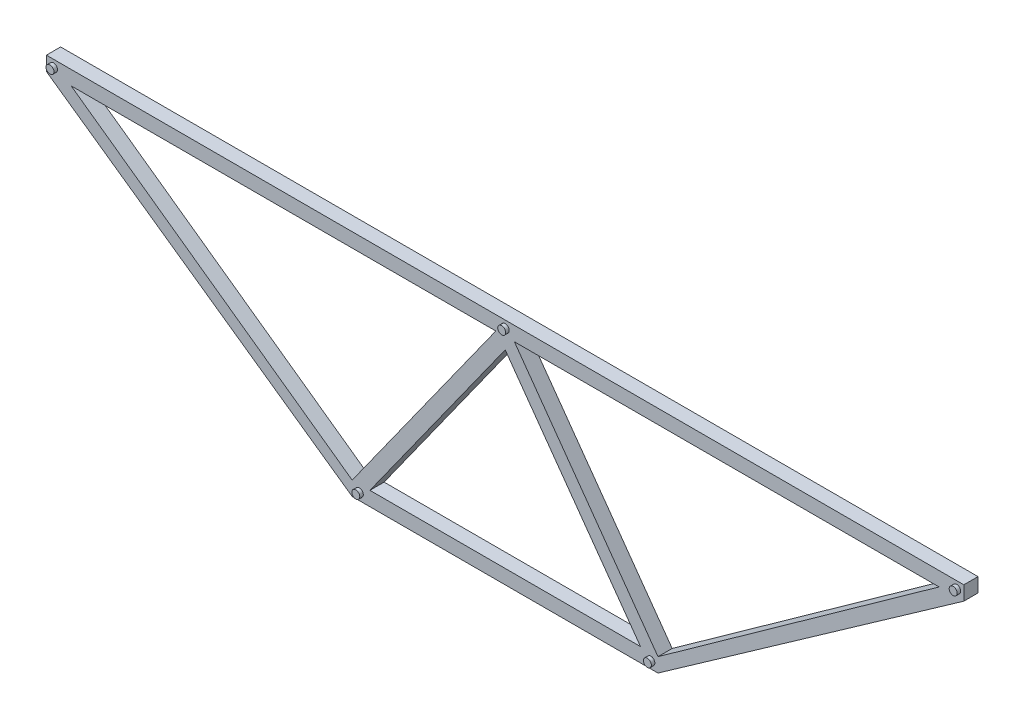
SolidWorks part; units mm, degrees
material "A 500 STEEL"
ref_plane "Front Plane" through (0, 0, 0) normal (0, 0, 1) x (1, 0, 0)
ref_plane "Top Plane" through (0, 0, 0) normal (0, 1, 0) x (1, 0, 0)
ref_plane "Right Plane" through (0, 0, 0) normal (1, 0, 0) x (0, 0, -1)
sketch "Sketch2" plane through (0, 0, 0) normal (0, 0, 1) x (1, 0, 0)
  line L0 (0, 0) -> (1200, 0)
  line L1 (0, 0) -> (0, -18.59)
  line L2 (0, -18.59) -> (400, -300)
  line L3 (400, -300) -> (800, -300)
  line L4 (800, -300) -> (1200, -18.59)
  line L5 (1200, -18.59) -> (1200, 0)
  dimension "D1" = 1200
  dimension "D2" = 18.59
  dimension "D3" = 300
  dimension "D4" = 400
extrude "Boss-Extrude1" add sketch "Sketch2" along normal blind 18.59
sketch "Sketch3" plane through (0, 0, 18.59) normal (0, 0, 1) x (1, 0, 0)
  line L0 (32.3082, 0) -> (32.3082, -18.59) construction
  line L1 (1200, 0) -> (0, 0) construction
  line L2 (21.6116, -33.7943) -> (32.3082, -18.59) construction
  line L3 (0, -18.59) -> (400, -300) construction
  line L6 (400, -300) -> (400, -281.41) construction
  line L7 (32.3082, -18.59) -> (400, -281.41)
  line L8 (400, -281.41) -> (587.8594, -18.59)
  line L9 (587.8594, -18.59) -> (32.3082, -18.59)
  line L12 (556.1658, -62.9301) -> (571.2896, -73.7403) construction
  line L13 (600.1563, -33.7923) -> (423.1633, -281.41)
  line L14 (800, -300) -> (800, -281.41) construction
  line L15 (1178.3884, -33.7943) -> (1167.6918, -18.59) construction
  line L16 (800, -300) -> (1200, -18.59) construction
  line L17 (800, -281.41) -> (1167.6918, -18.59)
  line L18 (633.8432, -48.9525) -> (618.7195, -59.7627) construction
  line L19 (800, -281.41) -> (612.1406, -18.59)
  line L20 (612.1406, -18.59) -> (1167.6918, -18.59)
  line L21 (671.7379, -281.41) -> (671.7379, -300) construction
  line L22 (777.1493, -281.41) -> (423.1633, -281.41)
  line L23 (767.4609, 0) -> (767.4609, -18.59) construction
  line L24 (400, -300) -> (800, -300) construction
  line L25 (777.1493, -281.41) -> (600.1563, -33.7923)
  point P31 (589.5383, -18.59)
  point P33 (618.3916, -59.9931)
  point P34 (571.2896, -73.7403)
  dimension "D1" = 18.59
  dimension "D2" = 18.59
  dimension "D3" = 18.59
  dimension "D4" = 18.59
  dimension "D5" = 18.59
  dimension "D6" = 18.59
  dimension "D7" = 18.59
  dimension "D8" = 18.59
  dimension "D9" = 18.59
extrude "Cut-Extrude2" cut sketch "Sketch3" against normal through all
sketch "Sketch4" plane through (0, 0, 0) normal (0, 0, -1) x (-1, 0, 0)
  line L0 (-1200, 0) -> (0, 0) construction
  line L1 (-1200, -18.59) -> (-1200, 0) construction
  line L2 (0, 0) -> (0, -18.59) construction
  line L3 (-400, -300) -> (-800, -300) construction
  circle A0 centre (-1190.705, -9.295) radius 5.207
  circle A1 centre (-600.1563, -9.295) radius 5.207
  circle A2 centre (-9.295, -9.295) radius 5.207
  circle A3 centre (-790.705, -290.705) radius 5.207
  circle A4 centre (-409.295, -290.705) radius 5.207
  dimension "D3" = 10.414
  dimension "D4" = 9.295
  dimension "D1" = 9.295
  dimension "D2" = 9.295
  dimension "D5" = 9.295
  dimension "D6" = 9.295
  dimension "D7" = 9.295
extrude "Boss-Extrude3" add sketch "Sketch4" against normal blind 23.2
